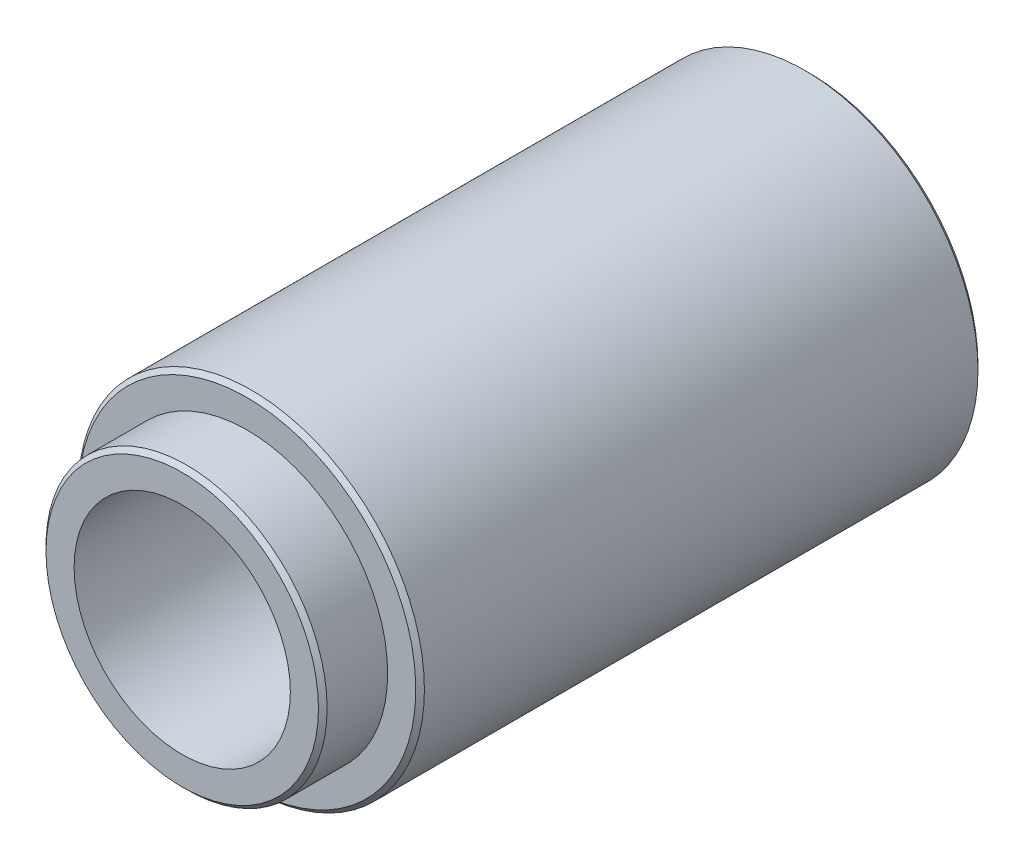
SolidWorks part; units mm, degrees
ref_plane "Ebene vorne" through (0, 0, 0) normal (0, 0, 1) x (1, 0, 0)
ref_plane "Ebene oben" through (0, 0, 0) normal (0, 1, 0) x (1, 0, 0)
ref_plane "Ebene rechts" through (0, 0, 0) normal (1, 0, 0) x (0, 0, -1)
sketch "Skizze1" plane through (0, 0, 0) normal (0, 0, 1) x (1, 0, 0)
  circle A0 centre (0, 0) radius 8
  dimension "D1" = 16
extrude "Aufsatz-Linear austragen1" add sketch "Skizze1" along normal blind 26
sketch "Skizze2" plane through (0, 0, 26) normal (0, 0, 1) x (1, 0, 0)
  circle A0 centre (0, 0) radius 6.5
  dimension "D1" = 13
extrude "Aufsatz-Linear austragen2" add sketch "Skizze2" along normal blind 3
sketch "Skizze3" plane through (0, 0, 0) normal (0, 0, -1) x (-1, 0, 0)
  circle A0 centre (0, 0) radius 5
  dimension "D1" = 10
extrude "Schnitt-Linear austragen1" cut sketch "Skizze3" against normal through all both and the other way through all
chamfer "Fase1" distance 0.2 angle 45 3 edges at (8, 0, 0) (8, 0, 26) (6.5, 0, 29)
